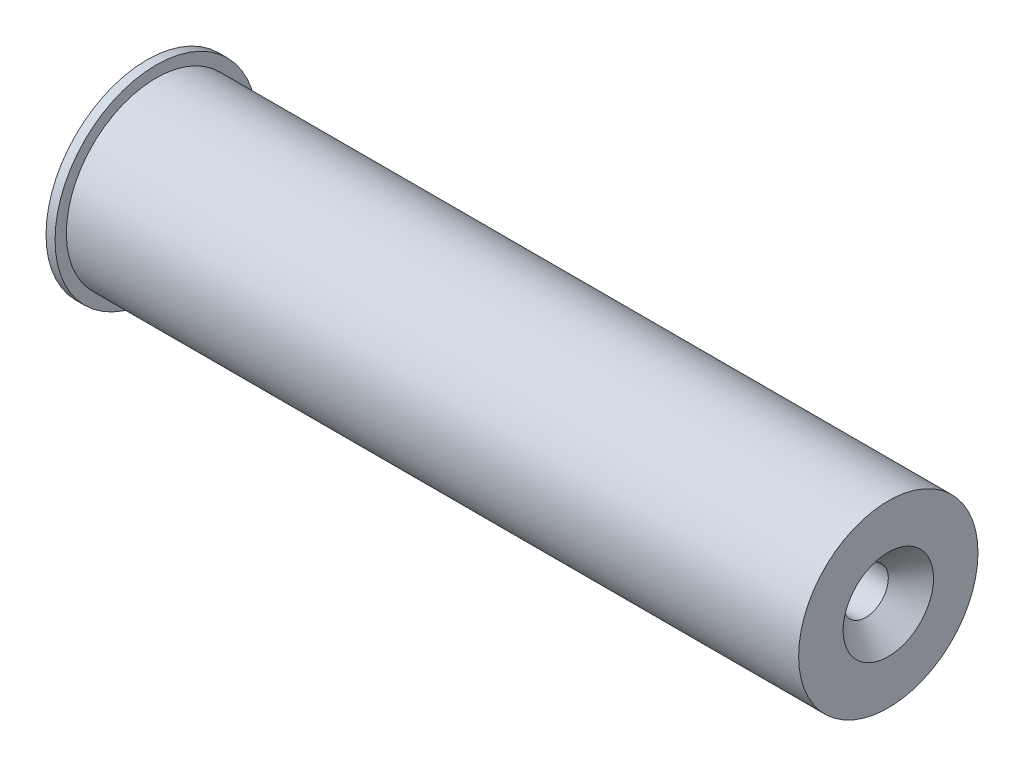
SolidWorks part; units mm, degrees
ref_plane "Front Plane" through (0, 0, 0) normal (0, 0, 1) x (1, 0, 0)
ref_plane "Top Plane" through (0, 0, 0) normal (0, 1, 0) x (1, 0, 0)
ref_plane "Right Plane" through (0, 0, 0) normal (1, 0, 0) x (0, 0, -1)
sketch "Sketch1" plane through (0, 0, 0) normal (1, 0, 0) x (0, 0, -1)
  circle A0 centre (0, 0) radius 25.2
  dimension "D1" = 50.4
extrude "Boss-Extrude1" add sketch "Sketch1" along normal blind 208.28
sketch "Sketch2" plane through (0, 0, 0) normal (-1, 0, 0) x (0, 0, 1)
  circle A0 centre (0, 0) radius 28.375
  circle A1 centre (0, 0) radius 25.2 construction
  dimension "D1" = 3.175
extrude "Boss-Extrude2" add sketch "Sketch2" against normal blind 2.54
sketch "Sketch4" plane through (208.28, 0, 0) normal (1, 0, 0) x (0, 0, -1)
  circle A0 centre (0, 0) radius 6.35
  dimension "D1" = 12.7
extrude "Cut-Extrude1" cut sketch "Sketch4" against normal through all
chamfer "Chamfer1" distance 6.35 angle 45 1 edges at (208.28, 0, -6.35)
